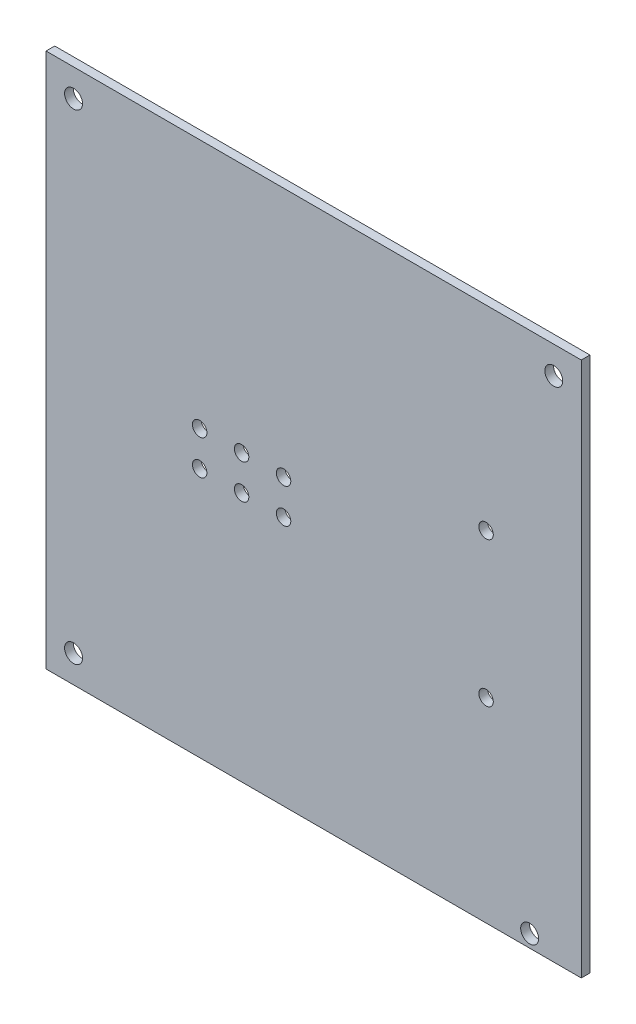
SolidWorks part; units mm, degrees
material "FR4"
ref_plane "Front Plane" through (0, 0, 0) normal (0, 0, 1) x (1, 0, 0)
ref_plane "Top Plane" through (0, 0, 0) normal (0, 1, 0) x (1, 0, 0)
ref_plane "Right Plane" through (0, 0, 0) normal (1, 0, 0) x (0, 0, -1)
sketch "Sketch1" plane through (0, 0, 0) normal (0, 0, 1) x (1, 0, 0)
  line L1 (46.25, -46.25) -> (-46.25, -46.25)
  line L2 (46.25, -46.25) -> (46.25, 46.25)
  line L3 (46.25, 46.25) -> (-46.25, 46.25)
  line L4 (-46.25, -46.25) -> (-46.25, 46.25)
  line L5 (46.25, -46.25) -> (-46.25, 46.25) construction
  line L6 (46.25, 46.25) -> (-46.25, -46.25) construction
  point P0 (0, 0)
  dimension "D1" = 92.5
  dimension "D2" = 92.5
extrude "Boss-Extrude1" add sketch "Sketch1" along normal blind 1.5
hole_wizard "Ø3.1 (3.1) Diameter Hole1" positions "Sketch3" profile "Sketch2" hole size "Ø3.1" standard "ANSI Metric" end condition through all
sketch "Sketch3" plane through (0, 0, 1.5) normal (0, 0, 1) x (1, 0, 0)
  point P0 (-41.5, 41.5)
  point P2 (41.5, 41.5)
  point P4 (37.33, -44.05)
  point P6 (-41.5, -41.5)
sketch "Sketch2" plane through (-41.5, 41.5, 1.5) normal (1, 0, 0) x (0, -1, 0)
  line L0 (0, 0) -> (0, 1.5)
  line L1 (0, 1.5) -> (1.55, 1.5)
  line L2 (1.55, 1.5) -> (1.55, 0)
  line L5 (1.55, 0) -> (0, 0)
  line L11 (0, -6.35) -> (0, 107.95) construction
  dimension "Thru Hole Dia." = 3.1
  dimension "Thru Hole Depth" = 1.5
hole_wizard "Ø2.5 (2.5) Diameter Hole1" positions "Sketch5" profile "Sketch4" hole size "Ø2.5" standard "ANSI Metric" end condition through all
sketch "Sketch5" plane through (0, 0, 0) normal (0, 0, -1) x (-1, 0, 0)
  point P0 (19.705, 3)
  point P2 (19.705, -3)
  point P4 (12.455, -3)
  point P6 (12.455, 3)
  point P8 (5.205, 3)
  point P10 (5.205, -3)
  point P13 (-29.795, 12.502)
  point P16 (-29.795, -12.5018)
sketch "Sketch4" plane through (-19.705, 3, 0) normal (1, 0, 0) x (0, 1, 0)
  line L0 (0, 0) -> (0, 1.5)
  line L1 (0, 1.5) -> (1.25, 1.5)
  line L2 (1.25, 1.5) -> (1.25, 0)
  line L5 (1.25, 0) -> (0, 0)
  line L11 (0, -6.35) -> (0, 107.95) construction
  dimension "Thru Hole Dia." = 2.5
  dimension "Thru Hole Depth" = 1.5
